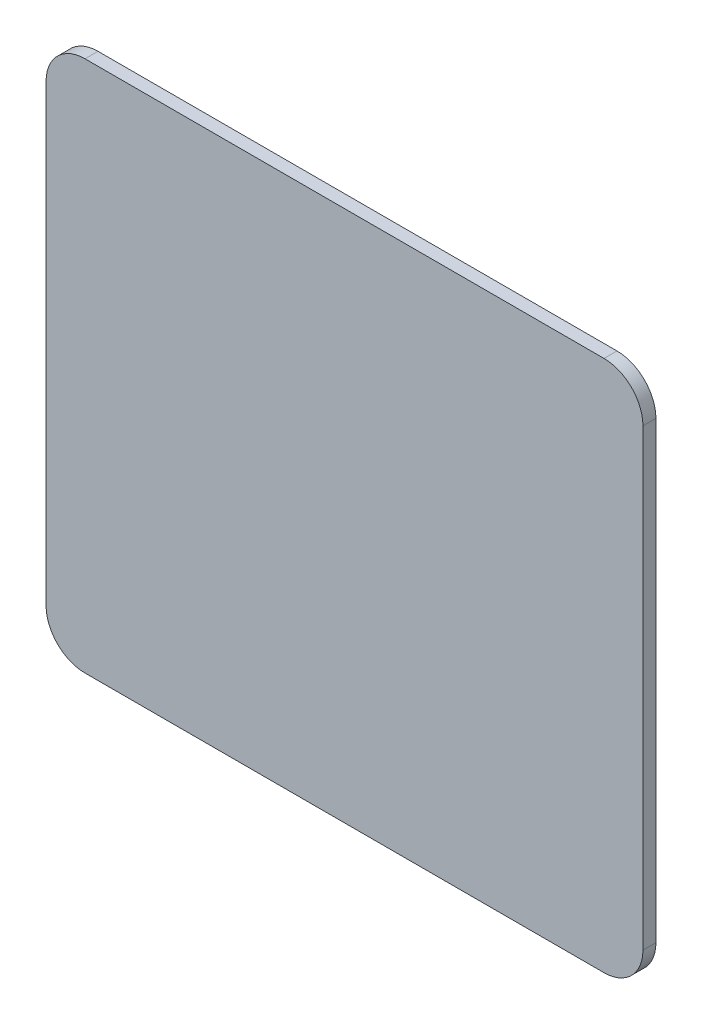
SolidWorks part; units mm, degrees
material "Vidro"
ref_plane "Plano frontal" through (0, 0, 0) normal (0, 0, 1) x (1, 0, 0)
ref_plane "Plano superior" through (0, 0, 0) normal (0, 1, 0) x (1, 0, 0)
ref_plane "Plano direito" through (0, 0, 0) normal (1, 0, 0) x (0, 0, -1)
sketch "Esboço1" plane through (0, 0, 0) normal (0, 0, 1) x (1, 0, 0)
  line L0 (-22.1582, 19.0252) -> (-22.1582, -15.9748)
  line L1 (-19.1582, -18.9748) -> (20.8418, -18.9748)
  line L2 (23.8418, -15.9748) -> (23.8418, 19.0252)
  line L3 (20.8418, 22.0252) -> (-19.1582, 22.0252)
  arc A0 (-22.1582, 19.0252) -> (-19.1582, 22.0252) centre (-19.1582, 19.0252) cw
  arc A1 (20.8418, 22.0252) -> (23.8418, 19.0252) centre (20.8418, 19.0252) cw
  arc A2 (23.8418, -15.9748) -> (20.8418, -18.9748) centre (20.8418, -15.9748) cw
  arc A3 (-19.1582, -18.9748) -> (-22.1582, -15.9748) centre (-19.1582, -15.9748) cw
extrude "Ressalto-extrusão1" add sketch "Esboço1" along normal blind 1
